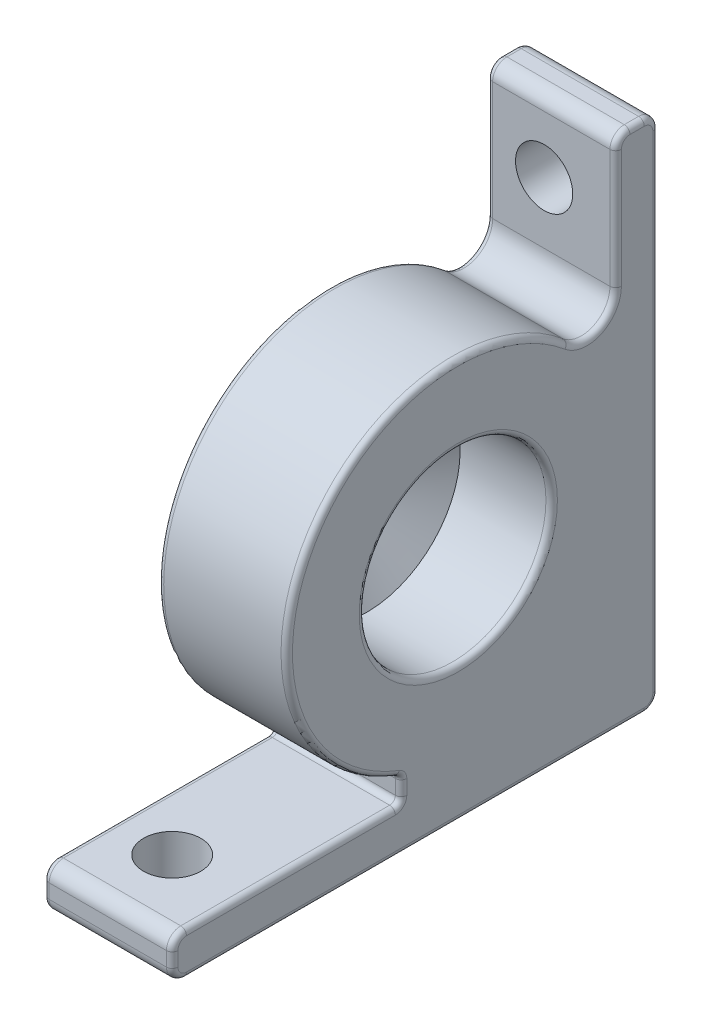
SolidWorks part; units mm, degrees
ref_plane "前视基准面" through (0, 0, 0) normal (0, 0, 1) x (1, 0, 0)
ref_plane "上视基准面" through (0, 0, 0) normal (0, 1, 0) x (1, 0, 0)
ref_plane "右视基准面" through (0, 0, 0) normal (1, 0, 0) x (0, 0, -1)
sketch "草图1" plane through (0, 0, 0) normal (1, 0, 0) x (0, 0, -1)
  line L0 (-9.5, -8) -> (6.5, -8)
  line L1 (-9.5, -6.5) -> (-2.2, -6.5)
  line L2 (-2, -5.7919) -> (-2, -6.3)
  line L3 (-10, -7) -> (-10, -7.5)
  line L4 (5.5, 9.5) -> (5.5, 5.3562)
  line L5 (-2.2, -6.5) -> (-9.5, -6.5)
  line L6 (7, 9.5) -> (7, -7.5)
  line L8 (6.5, 10) -> (6, 10)
  arc A0 (3.8567, 4.5905) -> (-2.129, -5.6049) centre (0, 0) ccw
  arc A1 (-2, -5.7919) -> (-2.129, -5.6049) centre (-2.2, -5.7919) ccw
  arc A2 (6.5, 10) -> (7, 9.5) centre (6.5, 9.5) cw
  arc A3 (-2, -6.3) -> (-2.2, -6.5) centre (-2.2, -6.3) cw
  arc A4 (5.5, 9.5) -> (6, 10) centre (6, 9.5) cw
  arc A5 (5.5, 5.3562) -> (3.8567, 4.5905) centre (4.5, 5.3562) cw
  arc A6 (7, -7.5) -> (6.5, -8) centre (6.5, -7.5) cw
  arc A7 (-9.5, -8) -> (-10, -7.5) centre (-9.5, -7.5) cw
  arc A8 (-9.5, -6.5) -> (-10, -7) centre (-9.5, -7) ccw
  point P14 (3.9686, -4.5)
  dimension "D1" = 8
  dimension "D2" = 6.5
  dimension "D3" = 0.5
  dimension "D5" = 7
  dimension "D7" = 1
  dimension "D9" = 0.5
extrude "凸台-拉伸1" add sketch "草图1" along normal blind 4.5 contours L1 A8 L3 A7 L0 A6 L6 A2 L8 A4 L4 A5 A0 A1 L2 A3
sketch "草图2" plane through (0, 0, 0) normal (-1, 0, 0) x (0, 0, 1)
  circle A0 centre (0, 0) radius 2
extrude "切除-拉伸1" cut sketch "草图2" against normal blind 10
hole_wizard "5/16-18 螺纹孔1" positions "草图3" profile "草图4" tap size "5/16-18" standard "ANSI Inch"
sketch "草图3" plane through (4.5, 0, 0) normal (1, 0, 0) x (0, 0, -1)
  point P0 (0, 0)
sketch "草图4" plane through (4.5, 0, 0) normal (0, 1, 0) x (0, 0, -1)
  line L0 (0, 0) -> (0, 5.1611)
  line L1 (0, 5.1611) -> (3.2639, 3.2)
  line L2 (3.2639, 3.2) -> (3.2639, 0)
  line L5 (3.2639, 0) -> (0, 0)
  line L10 (0, 5.1611) -> (-3.2639, 3.2) construction
  line L11 (0, -6.35) -> (0, 107.95) construction
  dimension "螺纹孔钻头直径" = 6.5278
  dimension "螺纹孔钻头深度" = 3.2
  dimension "导头角度" = 118
cosmetic thread "孔螺蚊线1" parameters "D1"=3.2, "D2"=7.9375
sketch "草图5" plane through (0, -6.5, 0) normal (0, 1, 0) x (1, 0, 0)
  circle A0 centre (2, -7.5) radius 1
extrude "切除-拉伸2" cut sketch "草图5" against normal up to next
sketch "草图6" plane through (0, 0, -5.5) normal (0, 0, 1) x (1, 0, 0)
  circle A0 centre (2, 7.5) radius 1
extrude "切除-拉伸3" cut sketch "草图6" against normal up to next
fillet "圆角1" radius 0.2 34 edges at (0, -6.6464, 9.8536) (0, -7.25, 10) (0, -7.8536, 9.8536) (0, -8, 1.5) (0, -7.8536, -6.8536) (0, 1, -7) (0, 9.8536, -6.8536) (0, 10, -6.25) (0, 9.8536, -5.6464) (0, 7.4281, -5.5) (0, 4.4497, -4.9223) (0, 3.0355, 5.1704) (0, -5.6783, 2.0354) (0, -6.0459, 2) (0, -6.4414, 2.0586) (0, -6.5, 5.85) (0, 0, 2) (4.5, -6.4414, 2.0586) (4.5, -6.0459, 2) (4.5, -5.6783, 2.0354) (4.5, 3.0355, 5.1704) (4.5, 4.4497, -4.9223) (4.5, 7.4281, -5.5) (4.5, 9.8536, -5.6464) (4.5, 10, -6.25) (4.5, 9.8536, -6.8536) (4.5, 1, -7) (4.5, -7.8536, -6.8536) (4.5, -8, 1.5) (4.5, -7.8536, 9.8536) (4.5, -7.25, 10) (4.5, -6.6464, 9.8536) (4.5, -6.5, 5.85) (4.5, 0, -3.2639)
